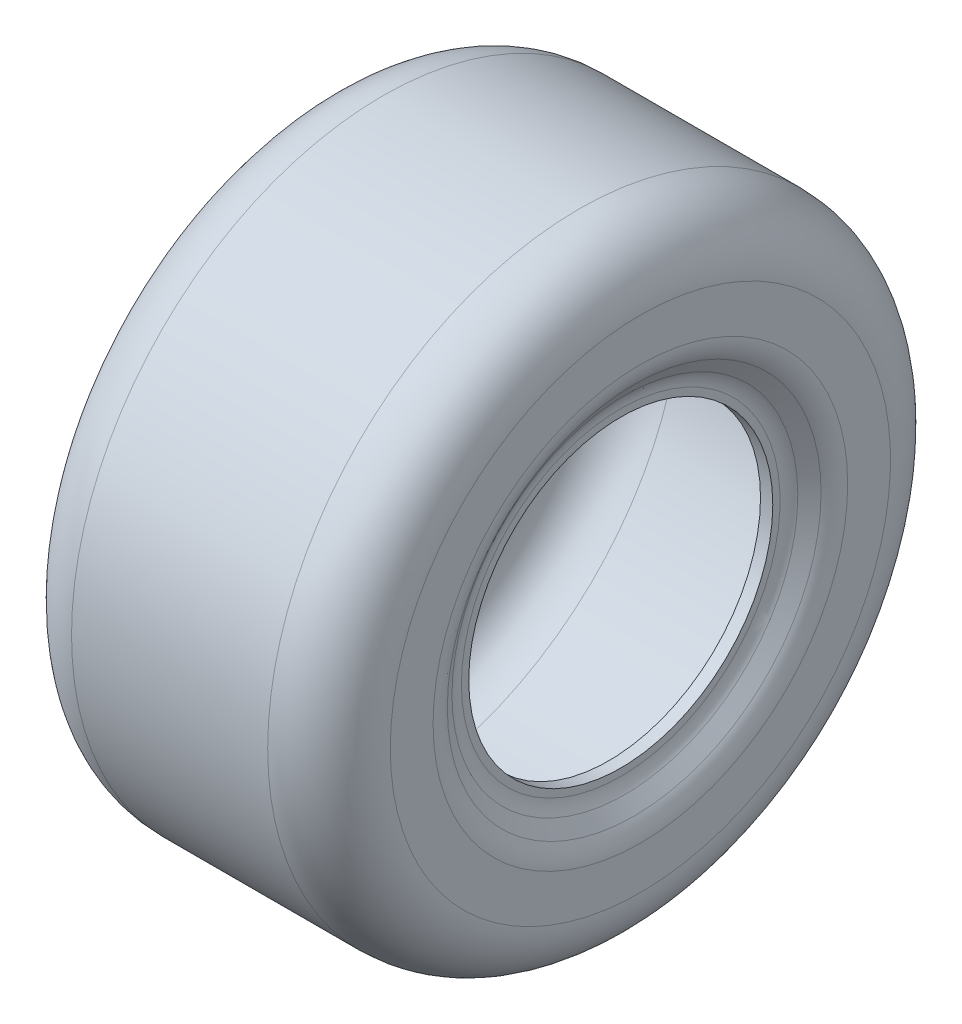
SolidWorks part; units mm, degrees
material "Rubber"
ref_plane "Front Plane" through (0, 0, 0) normal (0, 0, 1) x (1, 0, 0)
ref_plane "Top Plane" through (0, 0, 0) normal (0, 1, 0) x (1, 0, 0)
ref_plane "Right Plane" through (0, 0, 0) normal (1, 0, 0) x (0, 0, -1)
sketch "Sketch1" plane through (0, 0, 0) normal (0, 0, 1) x (1, 0, 0)
  line L0 (-65, 0) -> (65, 0) construction
  line L1 (0, 0) -> (0, 62) construction
  line L2 (0, 62) -> (-57, 62) construction
  line L3 (0, 62) -> (0, 127) construction
  line L4 (-57, 62) -> (-57, 68) construction
  point P4 (0, 0)
  dimension "D1" = 130
  dimension "D2" = 62
  dimension "D3" = 57
  dimension "D4" = 127
  dimension "D5" = 6
sketch "Sketch2" plane through (0, 0, 0) normal (0, 0, 1) x (1, 0, 0)
  line L0 (0, 127) -> (-40, 127)
  line L1 (-65, 102) -> (-65, 84.5416)
  line L2 (-62.4808, 76.2211) -> (-58.6795, 70.5192)
  line L3 (-57, 64.9722) -> (-57, 62)
  line L4 (0, 122) -> (-40, 122)
  line L5 (-60, 102) -> (-60, 84.5416)
  line L6 (-58.3205, 78.9946) -> (-54.5192, 73.2927)
  line L7 (-52, 64.9722) -> (-52, 62)
  line L8 (-57, 62) -> (-52, 62)
  line L9 (0, 62) -> (-57, 62) construction
  line L10 (0, 62) -> (0, 127) construction
  line L11 (0, 62) -> (0, 127) construction
  line L12 (0, 122) -> (40, 122)
  line L13 (0, 127) -> (40, 127)
  line L14 (58.3205, 78.9946) -> (54.5192, 73.2927)
  line L15 (65, 102) -> (65, 84.5416)
  line L16 (60, 102) -> (60, 84.5416)
  line L17 (62.4808, 76.2211) -> (58.6795, 70.5192)
  line L18 (52, 64.9722) -> (52, 62)
  line L19 (57, 64.9722) -> (57, 62)
  line L20 (57, 62) -> (52, 62)
  arc A0 (-40, 127) -> (-65, 102) centre (-40, 102) ccw
  arc A1 (-65, 84.5416) -> (-62.4808, 76.2211) centre (-50, 84.5416) ccw
  arc A2 (-58.6795, 70.5192) -> (-57, 64.9722) centre (-67, 64.9722) cw
  arc A3 (-40, 122) -> (-60, 102) centre (-40, 102) ccw
  arc A4 (-60, 84.5416) -> (-58.3205, 78.9946) centre (-50, 84.5416) ccw
  arc A5 (-54.5192, 73.2927) -> (-52, 64.9722) centre (-67, 64.9722) cw
  arc A6 (40, 127) -> (65, 102) centre (40, 102) cw
  arc A7 (40, 122) -> (60, 102) centre (40, 102) cw
  arc A8 (60, 84.5416) -> (58.3205, 78.9946) centre (50, 84.5416) cw
  arc A9 (65, 84.5416) -> (62.4808, 76.2211) centre (50, 84.5416) cw
  arc A10 (58.6795, 70.5192) -> (57, 64.9722) centre (67, 64.9722) ccw
  arc A11 (54.5192, 73.2927) -> (52, 64.9722) centre (67, 64.9722) ccw
  point P10 (-65, 127)
  point P12 (-65, 127)
  point P15 (-65, 80)
  point P18 (-57, 68)
  point P31 (-57.8027, 62)
  dimension "D2" = 80
  dimension "D3" = 25
  dimension "D4" = 15
  dimension "D5" = 10
  dimension "D1" = 65
  dimension "D6" = 5
revolve "Revolve1" add sketch "Sketch2" angle 360 about L0
